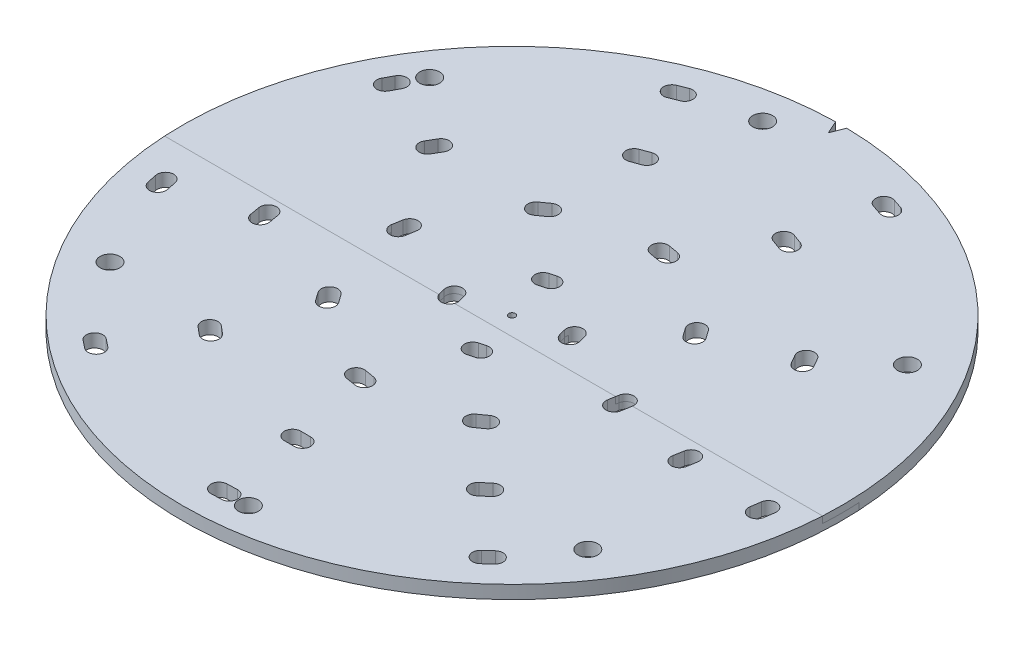
SolidWorks part; units mm, degrees
ref_plane "Alzado" through (0, 0, 0) normal (0, 0, 1) x (1, 0, 0)
ref_plane "Planta" through (0, 0, 0) normal (0, 1, 0) x (1, 0, 0)
ref_plane "Vista lateral" through (0, 0, 0) normal (1, 0, 0) x (0, 0, -1)
sketch "Croquis1" plane through (0, 0, 0) normal (0, 1, 0) x (1, 0, 0)
  line L0 (0, 0) -> (0, 100) construction
  line L1 (0, 0) -> (86.6025, 50) construction
  line L2 (0, 0) -> (86.6025, -50) construction
  line L3 (0, 0) -> (0, -100) construction
  line L4 (0, 0) -> (-86.6025, -50) construction
  line L5 (0, 0) -> (-86.6025, 50) construction
  circle A0 centre (0, 0) radius 100
  point P11 (0, 0)
  dimension "D1" = 200
  dimension "D2" = 6
extrude "Saliente-Extruir1" add sketch "Croquis1" along normal blind 4
sketch "Croquis2" plane through (0, 4, 0) normal (0, 1, 0) x (1, 0, 0)
  line L0 (0, 0) -> (0, 100) construction
  line L1 (0, 0) -> (86.6025, 50) construction
  line L2 (0, 0) -> (86.6025, -50) construction
  line L3 (0, 0) -> (0, -100) construction
  line L4 (0, 0) -> (-86.6025, -50) construction
  line L5 (0, 0) -> (-86.6025, 50) construction
  line L6 (-1.7732, 99.9843) -> (0, 95.9884)
  line L7 (0, 95.9884) -> (1.6104, 99.987)
  line L8 (-1.7732, 99.9843) -> (0, 102.3106)
  line L9 (0, 102.3106) -> (1.6104, 99.987)
  circle A0 centre (0, 0) radius 1
  circle A1 centre (0, 0) radius 100 construction
  point P14 (0, 0)
  dimension "D1" = 2
  dimension "D2" = 6
extrude "Cortar-Extruir1" cut sketch "Croquis2" against normal through all
sketch "Croquis3" plane through (0, 4, 0) normal (0, 1, 0) x (1, 0, 0)
  line L0 (0, 95.9884) -> (0, -100) construction
  line L1 (-100, 0) -> (100, 0) construction
  arc A0 (-1.7732, 99.9843) -> (1.6104, 99.987) centre (0, 0) ccw construction
  circle A1 centre (-13, 89.0562) radius 3
  circle A2 centre (0, 0) radius 90 construction
  circle A3 centre (73, 47) radius 3
  circle A4 centre (73, -50) radius 3
  circle A5 centre (10, -90) radius 3
  circle A6 centre (-75, 50) radius 3
  circle A7 centre (-75, -47) radius 3
  dimension "D2" = 180
  dimension "D3" = 6
  dimension "D6" = 6
  dimension "D7" = 6
  dimension "D12" = 6
  dimension "D13" = 6
  dimension "D16" = 6
  dimension "D18" = 47
  dimension "D1" = 13
  dimension "D4" = 47
  dimension "D5" = 73
  dimension "D8" = 73
  dimension "D9" = 50
  dimension "D10" = 10
  dimension "D11" = 90
  dimension "D14" = 50
  dimension "D15" = 75
  dimension "D17" = 75
extrude "Cortar-Extruir2" cut sketch "Croquis3" against normal through all
sketch "Croquis4" plane through (0, 4, 0) normal (0, 1, 0) x (1, 0, 0)
  line L0 (-79.9139, 41.3977) -> (-78.4898, 44.0381) construction
  line L1 (-82.1143, 42.5845) -> (-80.6901, 45.2249)
  line L2 (-77.7135, 40.2109) -> (-76.2894, 42.8513)
  line L3 (-34.5983, 83.0982) -> (-31.8101, 84.2055) construction
  line L4 (-35.521, 85.4217) -> (-32.7329, 86.529)
  line L5 (-33.6756, 80.7747) -> (-30.8874, 81.882)
  line L6 (26.92, 85.9144) -> (29.7677, 84.9704) construction
  line L7 (27.7067, 88.2874) -> (30.5543, 87.3434)
  line L8 (26.1334, 83.5414) -> (28.981, 82.5974)
  line L12 (89.312, -11.5663) -> (88.8768, -14.5345) construction
  line L13 (91.7855, -11.9289) -> (91.3504, -14.8972)
  line L14 (86.8384, -11.2036) -> (86.4032, -14.1719)
  line L15 (60.9917, -66.2508) -> (58.7503, -68.2449) construction
  line L16 (62.6534, -68.1186) -> (60.4121, -70.1127)
  line L17 (59.3299, -64.383) -> (57.0886, -66.3771)
  line L18 (4.1465, -89.9376) -> (1.1478, -90.0245) construction
  line L19 (4.2189, -92.4366) -> (1.2202, -92.5235)
  line L20 (4.0741, -87.4387) -> (1.0754, -87.5256)
  line L21 (-54.625, -71.5435) -> (-56.978, -69.6825) construction
  line L22 (-56.1758, -73.5043) -> (-58.5289, -71.6433)
  line L23 (-53.0742, -69.5826) -> (-55.4272, -67.7216)
  line L24 (-87.8231, -19.6751) -> (-88.4294, -16.737) construction
  line L25 (-90.2715, -20.1803) -> (-90.8778, -17.2422)
  line L26 (-85.3747, -19.1698) -> (-85.9809, -16.2317)
  line L27 (-55.4658, 33.8901) -> (-56.9705, 31.2948) construction
  line L28 (-53.303, 32.6362) -> (-54.8077, 30.0409)
  line L29 (-57.6287, 35.144) -> (-59.1333, 32.5486)
  line L30 (-20.7051, 61.6141) -> (-23.5261, 60.5931) construction
  line L31 (-19.8543, 59.2633) -> (-22.6752, 58.2423)
  line L32 (-21.556, 63.9649) -> (-24.3769, 62.9439)
  line L33 (23.7437, 60.5081) -> (20.9265, 61.5393) construction
  line L34 (22.8845, 58.1605) -> (20.0672, 59.1916)
  line L35 (24.603, 62.8558) -> (21.7858, 63.887)
  line L36 (57.0826, 31.0898) -> (55.5873, 33.6905) construction
  line L37 (54.9153, 29.8437) -> (53.42, 32.4444)
  line L38 (59.2499, 32.3359) -> (57.7546, 34.9366)
  line L39 (63.7119, -12.8759) -> (64.2382, -9.9224) construction
  line L40 (61.2507, -12.4373) -> (61.777, -9.4838)
  line L41 (66.1732, -13.3144) -> (66.6994, -10.3609)
  line L42 (40.5297, -50.8167) -> (42.8313, -48.8925) construction
  line L43 (38.9262, -48.8987) -> (41.2278, -46.9745)
  line L44 (42.1333, -52.7347) -> (44.4348, -50.8105)
  line L45 (-1.6168, -64.9799) -> (1.3832, -64.9853) construction
  line L46 (-1.6123, -62.4799) -> (1.3877, -62.4853)
  line L47 (-1.6213, -67.4799) -> (1.3787, -67.4853)
  line L48 (-43.0068, -48.7382) -> (-40.7121, -50.6707) construction
  line L49 (-41.3964, -46.826) -> (-39.1017, -48.7585)
  line L50 (-44.6172, -50.6504) -> (-42.3225, -52.5829)
  line L51 (-64.2735, -9.6914) -> (-63.7578, -12.6468) construction
  line L52 (-61.8107, -9.2617) -> (-61.295, -12.2171)
  line L53 (-66.7362, -10.1211) -> (-66.2206, -13.0765)
  line L54 (-39.1643, 8.1336) -> (-39.6638, 5.1755) construction
  line L55 (-36.6992, 7.7174) -> (-37.1987, 4.7593)
  line L56 (-41.6294, 8.5498) -> (-42.1289, 5.5917)
  line L57 (-21.942, 33.4447) -> (-24.3869, 31.7061) construction
  line L58 (-20.4932, 31.4073) -> (-22.9381, 29.6687)
  line L59 (-23.3908, 35.4821) -> (-25.8357, 33.7435)
  line L60 (8.1336, 39.1643) -> (5.1755, 39.6638) construction
  line L61 (7.7174, 36.6992) -> (4.7593, 37.1987)
  line L62 (8.5498, 41.6294) -> (5.5917, 42.1289)
  line L63 (33.4447, 21.942) -> (31.7061, 24.3869) construction
  line L64 (31.4073, 20.4932) -> (29.6687, 22.9381)
  line L65 (35.4821, 23.3908) -> (33.7435, 25.8357)
  line L66 (39.1643, -8.1336) -> (39.6638, -5.1755) construction
  line L67 (36.6992, -7.7174) -> (37.1987, -4.7593)
  line L68 (41.6294, -8.5498) -> (42.1289, -5.5917)
  line L69 (21.942, -33.4447) -> (24.3869, -31.7061) construction
  line L70 (20.4932, -31.4073) -> (22.9381, -29.6687)
  line L71 (23.3908, -35.4821) -> (25.8357, -33.7435)
  line L72 (-8.1336, -39.1643) -> (-5.1755, -39.6638) construction
  line L73 (-7.7174, -36.6992) -> (-4.7593, -37.1987)
  line L74 (-8.5498, -41.6294) -> (-5.5917, -42.1289)
  line L75 (-33.4447, -21.942) -> (-31.7061, -24.3869) construction
  line L76 (-31.4073, -20.4932) -> (-29.6687, -22.9381)
  line L77 (-35.4821, -23.3908) -> (-33.7435, -25.8357)
  line L78 (-14.2244, -4.761) -> (-14.7313, -2.8263) construction
  line L79 (-16.6427, -5.3947) -> (-17.1497, -3.46)
  line L80 (-11.806, -4.1273) -> (-12.313, -2.1926)
  line L81 (-4.761, 14.2244) -> (-2.8263, 14.7313) construction
  line L82 (-5.3947, 16.6427) -> (-3.46, 17.1497)
  line L83 (-4.1273, 11.806) -> (-2.1926, 12.313)
  line L84 (14.2244, 4.761) -> (14.7313, 2.8263) construction
  line L85 (16.6427, 5.3947) -> (17.1497, 3.46)
  line L86 (11.806, 4.1273) -> (12.313, 2.1926)
  line L87 (4.761, -14.2244) -> (2.8263, -14.7313) construction
  line L88 (5.3947, -16.6427) -> (3.46, -17.1497)
  line L89 (4.1273, -11.806) -> (2.1926, -12.313)
  line L99 (75.856, 48.5285) -> (77.4306, 45.9749) construction
  line L100 (77.984, 49.8407) -> (79.5586, 47.2871)
  line L101 (73.7281, 47.2163) -> (75.3027, 44.6628)
  line L102 (75.856, 48.5285) -> (77.4306, 45.9749) construction
  line L103 (77.984, 49.8407) -> (79.5586, 47.2871)
  line L104 (73.7281, 47.2163) -> (75.3027, 44.6628)
  circle A0 centre (0, 0) radius 90 construction
  circle A1 centre (0, 0) radius 15 construction
  circle A2 centre (0, 0) radius 65 construction
  circle A3 centre (0, 0) radius 40 construction
  arc A4 (-82.1143, 42.5845) -> (-77.7135, 40.2109) centre (-79.9139, 41.3977) ccw
  arc A5 (-76.2894, 42.8513) -> (-80.6901, 45.2249) centre (-78.4898, 44.0381) ccw
  arc A6 (-35.521, 85.4217) -> (-33.6756, 80.7747) centre (-34.5983, 83.0982) ccw
  arc A7 (-30.8874, 81.882) -> (-32.7329, 86.529) centre (-31.8101, 84.2055) ccw
  arc A8 (27.7067, 88.2874) -> (26.1334, 83.5414) centre (26.92, 85.9144) ccw
  arc A9 (28.981, 82.5974) -> (30.5543, 87.3434) centre (29.7677, 84.9704) ccw
  arc A12 (91.7855, -11.9289) -> (86.8384, -11.2036) centre (89.312, -11.5663) ccw
  arc A13 (86.4032, -14.1719) -> (91.3504, -14.8972) centre (88.8768, -14.5345) ccw
  arc A14 (62.6534, -68.1186) -> (59.3299, -64.383) centre (60.9917, -66.2508) ccw
  arc A15 (57.0886, -66.3771) -> (60.4121, -70.1127) centre (58.7503, -68.2449) ccw
  arc A16 (4.2189, -92.4366) -> (4.0741, -87.4387) centre (4.1465, -89.9376) ccw
  arc A17 (1.0754, -87.5256) -> (1.2202, -92.5235) centre (1.1478, -90.0245) ccw
  arc A18 (-56.1758, -73.5043) -> (-53.0742, -69.5826) centre (-54.625, -71.5435) ccw
  arc A19 (-55.4272, -67.7216) -> (-58.5289, -71.6433) centre (-56.978, -69.6825) ccw
  arc A20 (-90.2715, -20.1803) -> (-85.3747, -19.1698) centre (-87.8231, -19.6751) ccw
  arc A21 (-85.9809, -16.2317) -> (-90.8778, -17.2422) centre (-88.4294, -16.737) ccw
  arc A22 (-53.303, 32.6362) -> (-57.6287, 35.144) centre (-55.4658, 33.8901) ccw
  arc A23 (-59.1333, 32.5486) -> (-54.8077, 30.0409) centre (-56.9705, 31.2948) ccw
  arc A24 (-19.8543, 59.2633) -> (-21.556, 63.9649) centre (-20.7051, 61.6141) ccw
  arc A25 (-24.3769, 62.9439) -> (-22.6752, 58.2423) centre (-23.5261, 60.5931) ccw
  arc A26 (22.8845, 58.1605) -> (24.603, 62.8558) centre (23.7437, 60.5081) ccw
  arc A27 (21.7858, 63.887) -> (20.0672, 59.1916) centre (20.9265, 61.5393) ccw
  arc A28 (54.9153, 29.8437) -> (59.2499, 32.3359) centre (57.0826, 31.0898) ccw
  arc A29 (57.7546, 34.9366) -> (53.42, 32.4444) centre (55.5873, 33.6905) ccw
  arc A30 (61.2507, -12.4373) -> (66.1732, -13.3144) centre (63.7119, -12.8759) ccw
  arc A31 (66.6994, -10.3609) -> (61.777, -9.4838) centre (64.2382, -9.9224) ccw
  arc A32 (38.9262, -48.8987) -> (42.1333, -52.7347) centre (40.5297, -50.8167) ccw
  arc A33 (44.4348, -50.8105) -> (41.2278, -46.9745) centre (42.8313, -48.8925) ccw
  arc A34 (-1.6123, -62.4799) -> (-1.6213, -67.4799) centre (-1.6168, -64.9799) ccw
  arc A35 (1.3787, -67.4853) -> (1.3877, -62.4853) centre (1.3832, -64.9853) ccw
  arc A36 (-41.3964, -46.826) -> (-44.6172, -50.6504) centre (-43.0068, -48.7382) ccw
  arc A37 (-42.3225, -52.5829) -> (-39.1017, -48.7585) centre (-40.7121, -50.6707) ccw
  arc A38 (-61.8107, -9.2617) -> (-66.7362, -10.1211) centre (-64.2735, -9.6914) ccw
  arc A39 (-66.2206, -13.0765) -> (-61.295, -12.2171) centre (-63.7578, -12.6468) ccw
  arc A40 (-36.6992, 7.7174) -> (-41.6294, 8.5498) centre (-39.1643, 8.1336) ccw
  arc A41 (-42.1289, 5.5917) -> (-37.1987, 4.7593) centre (-39.6638, 5.1755) ccw
  arc A42 (-20.4932, 31.4073) -> (-23.3908, 35.4821) centre (-21.942, 33.4447) ccw
  arc A43 (-25.8357, 33.7435) -> (-22.9381, 29.6687) centre (-24.3869, 31.7061) ccw
  arc A44 (7.7174, 36.6992) -> (8.5498, 41.6294) centre (8.1336, 39.1643) ccw
  arc A45 (5.5917, 42.1289) -> (4.7593, 37.1987) centre (5.1755, 39.6638) ccw
  arc A46 (31.4073, 20.4932) -> (35.4821, 23.3908) centre (33.4447, 21.942) ccw
  arc A47 (33.7435, 25.8357) -> (29.6687, 22.9381) centre (31.7061, 24.3869) ccw
  arc A48 (36.6992, -7.7174) -> (41.6294, -8.5498) centre (39.1643, -8.1336) ccw
  arc A49 (42.1289, -5.5917) -> (37.1987, -4.7593) centre (39.6638, -5.1755) ccw
  arc A50 (20.4932, -31.4073) -> (23.3908, -35.4821) centre (21.942, -33.4447) ccw
  arc A51 (25.8357, -33.7435) -> (22.9381, -29.6687) centre (24.3869, -31.7061) ccw
  arc A52 (-7.7174, -36.6992) -> (-8.5498, -41.6294) centre (-8.1336, -39.1643) ccw
  arc A53 (-5.5917, -42.1289) -> (-4.7593, -37.1987) centre (-5.1755, -39.6638) ccw
  arc A54 (-31.4073, -20.4932) -> (-35.4821, -23.3908) centre (-33.4447, -21.942) ccw
  arc A55 (-33.7435, -25.8357) -> (-29.6687, -22.9381) centre (-31.7061, -24.3869) ccw
  arc A56 (-16.6427, -5.3947) -> (-11.806, -4.1273) centre (-14.2244, -4.761) ccw
  arc A57 (-12.313, -2.1926) -> (-17.1497, -3.46) centre (-14.7313, -2.8263) ccw
  arc A58 (-5.3947, 16.6427) -> (-4.1273, 11.806) centre (-4.761, 14.2244) ccw
  arc A59 (-2.1926, 12.313) -> (-3.46, 17.1497) centre (-2.8263, 14.7313) ccw
  arc A60 (16.6427, 5.3947) -> (11.806, 4.1273) centre (14.2244, 4.761) ccw
  arc A61 (12.313, 2.1926) -> (17.1497, 3.46) centre (14.7313, 2.8263) ccw
  arc A62 (5.3947, -16.6427) -> (4.1273, -11.806) centre (4.761, -14.2244) ccw
  arc A63 (2.1926, -12.313) -> (3.46, -17.1497) centre (2.8263, -14.7313) ccw
  arc A72 (77.984, 49.8407) -> (73.7281, 47.2163) centre (75.856, 48.5285) ccw
  arc A73 (75.3027, 44.6628) -> (79.5586, 47.2871) centre (77.4306, 45.9749) ccw
  point P8 (-79.2018, 42.7179)
  point P13 (-56.2182, 32.5924)
  point P18 (-33.2042, 83.6519)
  point P25 (28.3438, 85.4424)
  point P39 (89.0944, -13.0504)
  point P46 (59.871, -67.2478)
  point P53 (2.6471, -89.9811)
  point P60 (-55.8015, -70.613)
  point P67 (-88.1262, -18.206)
  point P72 (0.0295, -0.0038)
  point P77 (-22.1156, 61.1036)
  point P86 (22.3351, 61.0237)
  point P93 (56.335, 32.3901)
  point P100 (63.9751, -11.3991)
  point P107 (41.6805, -49.8546)
  point P114 (-0.1168, -64.9826)
  point P121 (-41.8595, -49.7045)
  point P128 (-64.0156, -11.1691)
  point P135 (0, 0)
  point P136 (-39.4141, 6.6545)
  point P145 (-23.1645, 32.5754)
  point P152 (6.6545, 39.4141)
  point P159 (32.5754, 23.1645)
  point P166 (39.4141, -6.6545)
  point P173 (23.1645, -32.5754)
  point P180 (-6.6545, -39.4141)
  point P187 (-32.5754, -23.1645)
  point P192 (0, 0)
  point P193 (-14.4778, -3.7937)
  point P203 (-3.7937, 14.4778)
  point P210 (14.4778, 3.7937)
  point P217 (3.7937, -14.4778)
  point P222 (0, 0)
  point P226 (76.6433, 47.2517)
  point P233 (76.6433, 47.2517)
  point P240 (76.6433, 47.2517)
  point P247 (76.6433, 47.2517)
  point P254 (76.6433, 47.2517)
  dimension "D1" = 180
  dimension "D2" = 30
  dimension "D3" = 130
  dimension "D4" = 80
  dimension "D14" = 2
  dimension "D5" = 3
  dimension "D6" = 5
  dimension "D8" = 3
  dimension "D9" = 5
  dimension "D11" = 3
  dimension "D12" = 5
  dimension "D15" = 5
  dimension "D7" = 9
  dimension "D10" = 9
  dimension "D13" = 8
  dimension "D16" = 4
extrude "Cortar-Extruir3" cut sketch "Croquis4" against normal through all
sketch "Croquis7" plane through (0, 0, 0) normal (1, 0, 0) x (0, 0, -1)
  line L0 (0, -5.076) -> (0, 9.3633) construction
  line L1 (-5.5917, 4) -> (-5.5917, 2)
  line L2 (-5.5917, 2) -> (5.3947, 2)
  line L3 (5.3947, 2) -> (5.3947, 0)
split "Partir1" trim tools "Croquis7" bodies to split 104 resulting bodies 105 106
